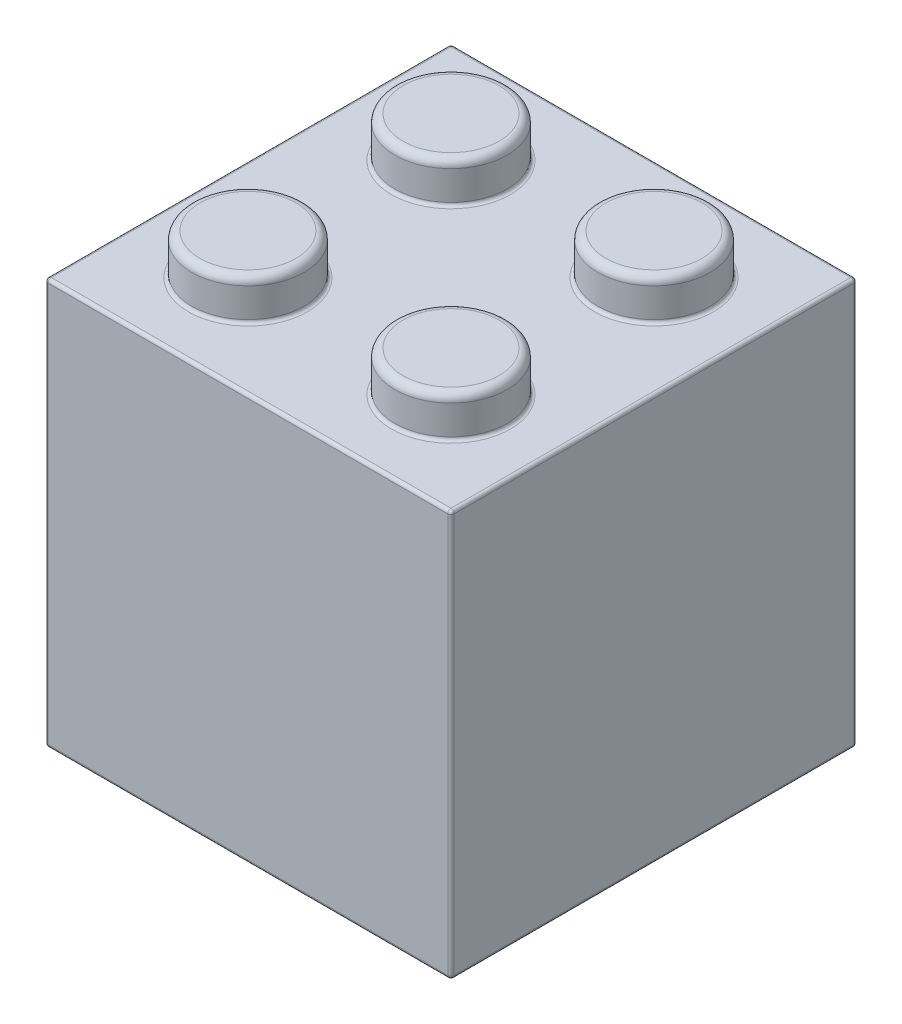
SolidWorks part; units mm, degrees
ref_plane "Front Plane" through (0, 0, 0) normal (0, 0, 1) x (1, 0, 0)
ref_plane "Top Plane" through (0, 0, 0) normal (0, 1, 0) x (1, 0, 0)
ref_plane "Right Plane" through (0, 0, 0) normal (1, 0, 0) x (0, 0, -1)
sketch "Sketch1" plane through (0, 0, 0) normal (0, 1, 0) x (1, 0, 0)
  line L1 (-8.3427, 5.5732) -> (1.6573, 5.5732)
  line L2 (-8.3427, 5.5732) -> (-8.3427, -4.4268)
  line L3 (-8.3427, -4.4268) -> (1.6573, -4.4268)
  line L4 (1.6573, 5.5732) -> (1.6573, -4.4268)
  point P4 (-2.0376, 2.9319)
  point P5 (1.6573, 5.5732)
  dimension "D1" = 10
extrude "box" add sketch "Sketch1" along normal blind 10
sketch "Sketch2" plane through (0, 0, 0) normal (0, -1, 0) x (1, 0, 0)
  line L8 (-7.8427, 3.9268) -> (-7.8427, -5.0732)
  line L9 (-7.8427, -5.0732) -> (1.1573, -5.0732)
  line L10 (1.1573, -5.0732) -> (1.1573, 3.9268)
  line L11 (1.1573, 3.9268) -> (-7.8427, 3.9268)
  line L12 (-7.8427, 3.9268) -> (-7.8427, -5.0732)
  line L13 (-7.8427, -5.0732) -> (1.1573, -5.0732)
  line L14 (1.1573, -5.0732) -> (1.1573, 3.9268)
  line L15 (1.1573, 3.9268) -> (-7.8427, 3.9268)
  dimension "D1" = 0.5
extrude "Cut-Extrude1" cut sketch "Sketch2" against normal blind 9.5
sketch "Sketch3" plane through (0, 10, 0) normal (0, 1, 0) x (1, 0, 0)
  line L0 (-8.3427, 5.5732) -> (-3.3427, 0.5732) construction
  line L1 (-3.3427, 0.5732) -> (1.6573, 5.5732) construction
  line L2 (-3.3427, 0.5732) -> (1.6573, -4.4268) construction
  line L3 (-3.3427, 0.5732) -> (-8.3427, -4.4268) construction
  circle A0 centre (-5.8427, 3.0732) radius 1.3841
  circle A1 centre (-0.8427, 3.0732) radius 1.3841
  circle A2 centre (-0.8427, -1.9268) radius 1.3841
  circle A3 centre (-5.8427, -1.9268) radius 1.3841
  point P20 (0, 0)
  point P21 (0, 0)
  point P22 (1.6573, 5.5732)
extrude "pins" add sketch "Sketch3" along normal blind 1
sketch "Sketch4" plane through (0, 9.5, 0) normal (0, -1, 0) x (1, 0, 0)
  circle A1 centre (-3.3427, -0.5732) radius 2.1515
  circle A2 centre (-0.8427, -3.0732) radius 1.3841 construction
  circle A3 centre (-0.8427, 1.9268) radius 1.3841 construction
  circle A4 centre (-5.8427, -3.0732) radius 1.3841 construction
  circle A6 centre (-5.8427, 1.9268) radius 1.3841 construction
  point P4 (0, 0)
  point P5 (-3.3427, -0.7095)
extrude "Boss-Extrude3" add sketch "Sketch4" along normal blind 9.4548
sketch "Sketch5" plane through (0, 0.0452, 0) normal (0, -1, 0) x (1, 0, 0)
  circle A0 centre (-3.3427, -0.5732) radius 1.8
  circle A1 centre (-3.3427, -0.5732) radius 2.1515 construction
  point P4 (-3.3427, -0.5732)
extrude "Cut-Extrude2" cut sketch "Sketch5" against normal blind 9.5
sketch "Sketch6" plane through (0, 9.5, 0) normal (0, -1, 0) x (1, 0, 0)
  circle A0 centre (-5.8427, 1.9268) radius 1.0864
  circle A1 centre (-0.8427, 1.9268) radius 1.0864
  circle A2 centre (-0.8427, -3.0732) radius 1.0864
  circle A3 centre (-5.8427, -3.0732) radius 1.0864
  circle A4 centre (-5.8427, 1.9268) radius 1.3841 construction
  circle A5 centre (-0.8427, 1.9268) radius 1.3841 construction
  circle A6 centre (-0.8427, -3.0732) radius 1.3841 construction
  circle A7 centre (-5.8427, -3.0732) radius 1.3841 construction
extrude "Cut-Extrude3" cut sketch "Sketch6" against normal blind 1
sketch "Sketch8" plane through (0, 9.5, 0) normal (0, -1, 0) x (1, 0, 0)
  line L0 (1.1573, 3.9268) -> (-7.8427, 3.9268) construction
  line L1 (-3.3427, 3.9268) -> (-7.8427, 3.9268) construction
  line L2 (-3.3427, 3.9268) -> (1.1573, 3.9268) construction
  line L3 (-6.0267, 3.9268) -> (-5.1586, 3.9268)
  line L4 (-7.8427, 3.9268) -> (1.1573, -5.0732) construction
  line L5 (-7.8427, -5.0732) -> (1.1573, 3.9268) construction
  line L6 (1.1573, 3.9268) -> (-1.3986, 2.4569) construction
  line L7 (-7.8427, 2.1108) -> (-7.8427, 1.2428)
  line L8 (-0.6586, -5.0732) -> (-1.5267, -5.0732)
  line L9 (1.1573, -3.2572) -> (1.1573, -2.3892)
  line L10 (-3.3427, 3.9268) -> (-3.3427, -5.0732) construction
  line L11 (-7.8427, -5.0732) -> (1.1573, -5.0732) construction
  line L12 (-6.0267, -5.0732) -> (-5.1586, -5.0732)
  line L13 (-7.8427, -3.2572) -> (-7.8427, -2.3892)
  line L14 (1.1573, 2.1108) -> (1.1573, 1.2428)
  line L15 (-0.6586, 3.9268) -> (-1.5267, 3.9268)
  arc A0 (-6.0267, 3.9268) -> (-5.1586, 3.9268) centre (-5.5927, 3.9268) ccw
  arc A1 (-7.8427, 2.1108) -> (-7.8427, 1.2428) centre (-7.8427, 1.6768) cw
  arc A2 (-0.6586, -5.0732) -> (-1.5267, -5.0732) centre (-1.0927, -5.0732) ccw
  arc A3 (1.1573, -3.2572) -> (1.1573, -2.3892) centre (1.1573, -2.8232) cw
  arc A4 (-6.0267, -5.0732) -> (-5.1586, -5.0732) centre (-5.5927, -5.0732) cw
  arc A5 (-7.8427, -3.2572) -> (-7.8427, -2.3892) centre (-7.8427, -2.8232) ccw
  arc A6 (1.1573, 2.1108) -> (1.1573, 1.2428) centre (1.1573, 1.6768) ccw
  arc A7 (-0.6586, 3.9268) -> (-1.5267, 3.9268) centre (-1.0927, 3.9268) cw
extrude "Boss-Extrude4" add sketch "Sketch8" along normal blind 9.5
fillet "Fillet5" radius 0.2 4 edges at (-0.8427, 11, 3.3109) (-0.8427, 11, -1.6891) (-5.8427, 11, -1.6891) (-5.8427, 11, 3.3109)
fillet "Fillet6" radius 0.08 38 edges at (-3.3427, 0.0452, -2.7247) (-3.3427, 0.0452, -2.3732) (-7.4086, 0, 1.6768) (-7.8427, 0, -0.5732) (-7.4086, 0, -2.8232) (-7.8427, 0, -4.1652) (-6.9347, 0, -5.0732) (-5.5927, 0, -4.6392) (-3.3427, 0, -5.0732) (-1.0927, 0, -4.6392) (0.2494, 0, -5.0732) (1.1573, 0, -4.1652) (0.7233, 0, -2.8232) (1.1573, 0, -0.5732) (0.7233, 0, 1.6768) (1.1573, 0, 3.0188) (0.2494, 0, 3.9268) (-1.0927, 0, 3.4928) (-3.3427, 0, 3.9268) (-5.5927, 0, 3.4928) (-6.9347, 0, 3.9268) (-7.8427, 0, 3.0188) (-3.3427, 0, -5.5732) (-8.3427, 5, -5.5732) (-8.3427, 0, -0.5732) (1.6573, 5, -5.5732) (1.6573, 0, -0.5732) (-8.3427, 5, 4.4268) (1.6573, 5, 4.4268) (-3.3427, 0, 4.4268) (-3.3427, 10, -5.5732) (1.6573, 10, -0.5732) (-3.3427, 10, 4.4268) (-8.3427, 10, -0.5732) (-5.8427, 10, -1.6891) (-0.8427, 10, -1.6891) (-0.8427, 10, 3.3109) (-5.8427, 10, 3.3109)
